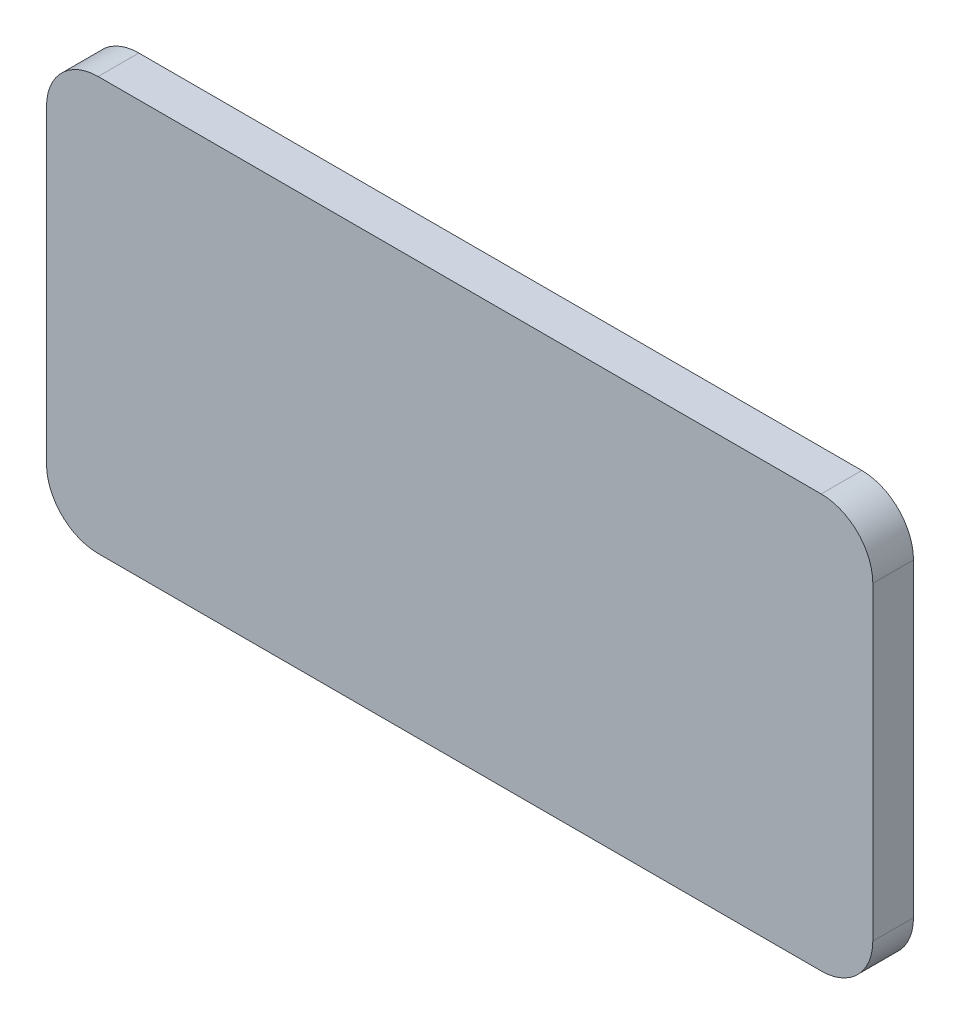
SolidWorks part; units mm, degrees
ref_plane "Front Plane" through (0, 0, 0) normal (0, 0, 1) x (1, 0, 0)
ref_plane "Top Plane" through (0, 0, 0) normal (0, 1, 0) x (1, 0, 0)
ref_plane "Right Plane" through (0, 0, 0) normal (1, 0, 0) x (0, 0, -1)
sketch "Sketch1" plane through (0, 0, 0) normal (0, 0, 1) x (1, 0, 0)
  line L1 (-20.32, -10.16) -> (20.32, -10.16)
  line L2 (-20.32, -10.16) -> (-20.32, 10.16)
  line L3 (-20.32, 10.16) -> (20.32, 10.16)
  line L4 (20.32, -10.16) -> (20.32, 10.16)
  line L5 (-20.32, -10.16) -> (20.32, 10.16) construction
  line L6 (-20.32, 10.16) -> (20.32, -10.16) construction
  point P0 (0, 0)
  dimension "D1" = 20.32
  dimension "D2" = 40.64
extrude "Boss-Extrude1" add sketch "Sketch1" along normal blind 2
fillet "Fillet1" radius 2.54 4 edges at (20.32, 10.16, 1) (20.32, -10.16, 1) (-20.32, 10.16, 1) (-20.32, -10.16, 1)
sketch "Sketch2" plane through (0, 0, 2) normal (0, 0, 1) x (1, 0, 0)
  line L1 (1.6402, -4.1217) -> (10.0478, -4.1217)
  line L2 (1.6402, -4.1217) -> (1.6402, 4.1217)
  line L3 (1.6402, 4.1217) -> (10.0478, 4.1217)
  line L4 (10.0478, -4.1217) -> (10.0478, 4.1217)
  line L5 (1.6402, -4.1217) -> (10.0478, 4.1217) construction
  line L6 (1.6402, 4.1217) -> (10.0478, -4.1217) construction
  point P0 (5.844, 0)
extrude "Boss-Extrude2" [suppressed] add sketch "Sketch2" along normal blind 5.588
sketch "Sketch3" plane through (0, 0, 0) normal (0, 0, 1) x (1, 0, 0)
  line L0 (20.32, 0) -> (-20.32, 0) construction
  line L1 (20.32, -7.62) -> (20.32, 7.62) construction
  line L2 (-20.32, 7.62) -> (-20.32, -7.62) construction
  line L3 (14.097, 0) -> (-7.8232, 0) construction
  line L4 (14.097, -7.1247) -> (-7.8232, -7.1247)
  line L5 (14.097, -7.1247) -> (14.097, 7.1247)
  line L6 (14.097, 7.1247) -> (-7.8232, 7.1247)
  line L7 (-7.8232, -7.1247) -> (-7.8232, 7.1247)
  dimension "D1" = 21.9202
  dimension "D2" = 14.2494
  dimension "D3" = 6.223
extrude "Boss-Extrude3" add sketch "Sketch3" against normal offset from surface (2.064 mm away) 4.064 up to face at (0, 0, 2)
